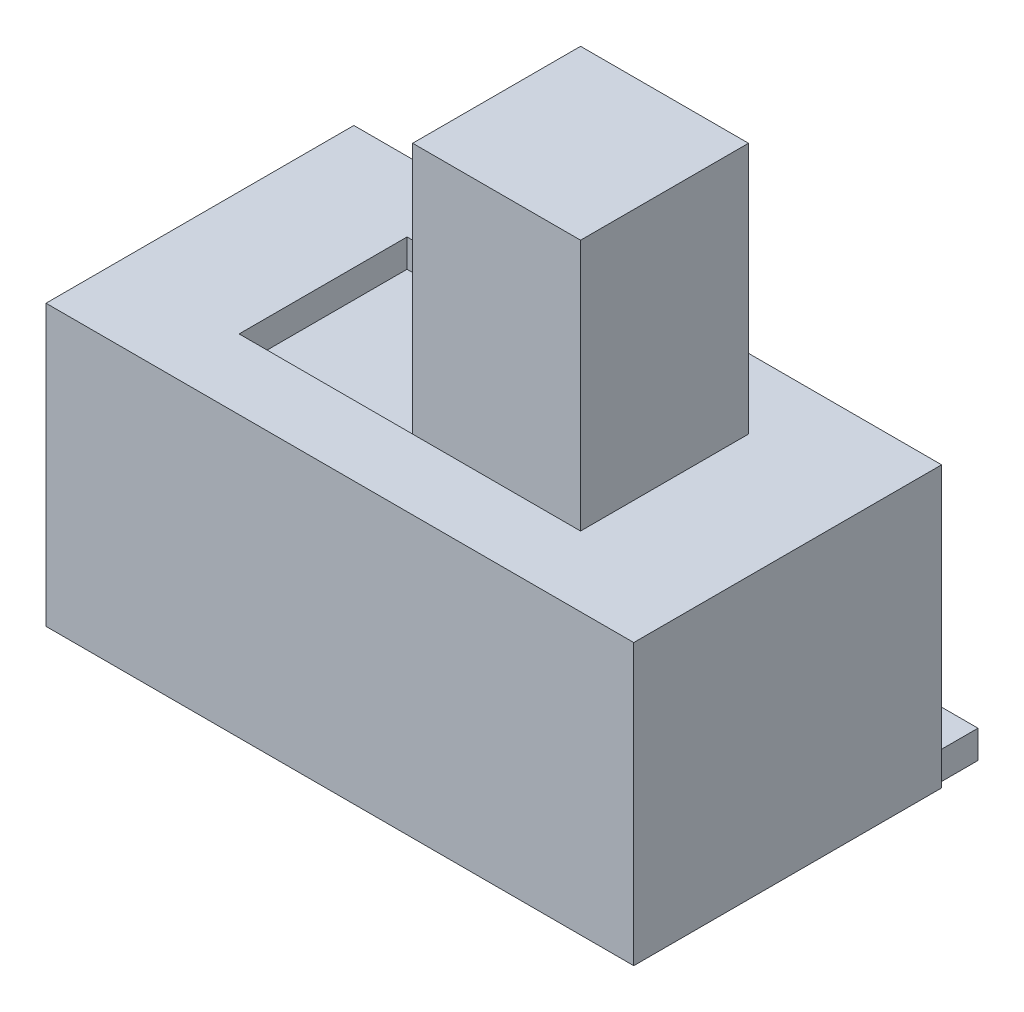
SolidWorks part; units mm, degrees
ref_plane "Front Plane" through (0, 0, 0) normal (0, 0, 1) x (1, 0, 0)
ref_plane "Top Plane" through (0, 0, 0) normal (0, 1, 0) x (1, 0, 0)
ref_plane "Right Plane" through (0, 0, 0) normal (1, 0, 0) x (0, 0, -1)
sketch "Sketch1" plane through (0, 0, 0) normal (0, 0, 1) x (1, 0, 0)
  line L1 (-5.25, 5) -> (5.25, 5)
  line L2 (-5.25, 5) -> (-5.25, 0)
  line L3 (-5.25, 0) -> (5.25, 0)
  line L4 (5.25, 5) -> (5.25, 0)
  dimension "D1" = 10.5
  dimension "D2" = 5
extrude "Boss-Extrude1" add sketch "Sketch1" along normal blind 5.5
sketch "Sketch2" plane through (0, 5, 0) normal (0, 1, 0) x (1, 0, 0)
  line L0 (0, 0) -> (0, -1.25) construction
  line L1 (-3.05, -1.25) -> (3.05, -1.25)
  line L2 (-3.05, -1.25) -> (-3.05, -4.25)
  line L3 (-3.05, -4.25) -> (3.05, -4.25)
  line L4 (3.05, -1.25) -> (3.05, -4.25)
  line L5 (3.05, -2.75) -> (5.25, -2.75) construction
  line L6 (5.25, -5.5) -> (5.25, 0) construction
  dimension "D1" = 6.1
  dimension "D2" = 3
extrude "Cut-Extrude1" cut sketch "Sketch2" against normal blind 0.5
sketch "Sketch3" plane through (0, 4.5, 0) normal (0, 1, 0) x (1, 0, 0)
  line L0 (-3.05, -4.25) -> (3.05, -4.25) construction
  line L1 (3.05, -1.25) -> (0.05, -1.25)
  line L2 (3.05, -1.25) -> (3.05, -4.25)
  line L3 (3.05, -4.25) -> (0.05, -4.25)
  line L4 (0.05, -1.25) -> (0.05, -4.25)
  dimension "D1" = 3
extrude "Boss-Extrude2" add sketch "Sketch3" along normal blind 5
sketch "Sketch4" plane through (0, 0, 0) normal (1, 0, 0) x (0, 0, -1)
  line L0 (-2.5, 0) -> (-2.5, -0.65)
  line L1 (-5.5, 0) -> (0, 0) construction
  line L2 (-2.5, 0) -> (-3, 0)
  line L3 (-1.9, -1.25) -> (2.5, -1.25)
  line L4 (2.5, -1.25) -> (2.5, -1.75)
  line L5 (2.5, -1.75) -> (-1.9, -1.75)
  line L6 (-3, 0) -> (-3, -0.65)
  line L7 (2.5, -1.5) -> (-4.8397, -1.5) construction
  line L8 (-5.5, 5) -> (0, 5) construction
  line L9 (-3, -0.65) -> (-2.5, -0.65) construction
  line L10 (0, 0) -> (0, 5) construction
  arc A0 (-2.5, -0.65) -> (-1.9, -1.25) centre (-1.9, -0.65) ccw
  arc A1 (-3, -0.65) -> (-1.9, -1.75) centre (-1.9, -0.65) ccw
  point P4 (-2.75, 0)
  dimension "D3" = 0.6
  dimension "D1" = 0.5
  dimension "D2" = 6.5
  dimension "D4" = 2.5
extrude "Boss-Extrude3" add sketch "Sketch4" along normal mid plane 0.8
pattern_linear "LPattern1" count 2 spacing 3 along (-1, 0, 0) count 2 spacing 3 along (1, 0, 0) of "Boss-Extrude3"
